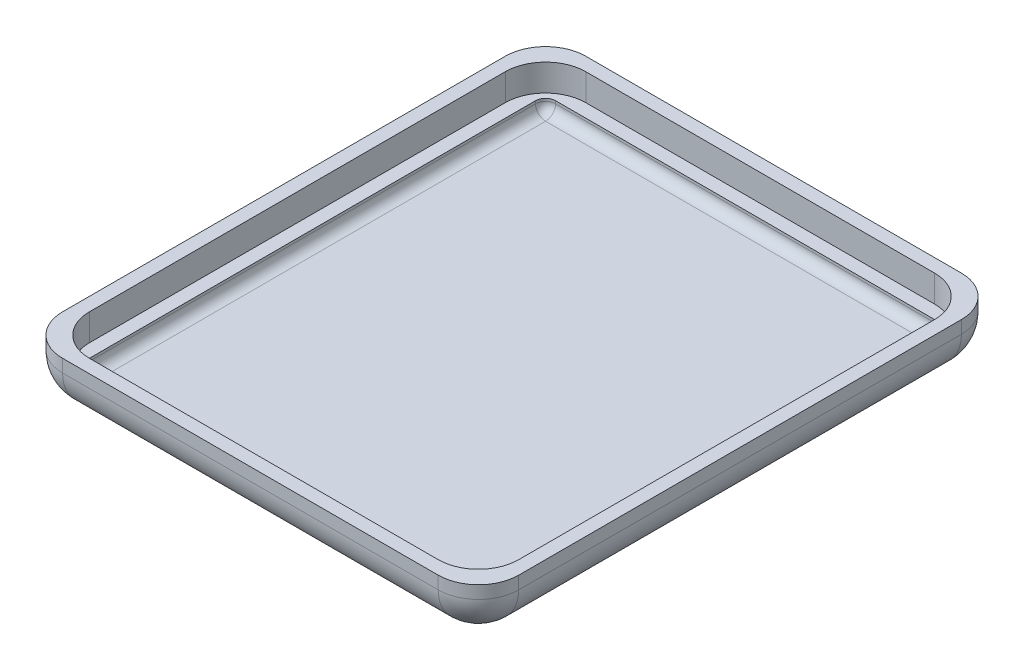
SolidWorks part; units mm, degrees
ref_plane "Piano frontale" through (0, 0, 0) normal (0, 0, 1) x (1, 0, 0)
ref_plane "Piano superiore" through (0, 0, 0) normal (0, 1, 0) x (1, 0, 0)
ref_plane "Piano destro" through (0, 0, 0) normal (1, 0, 0) x (0, 0, -1)
sketch "Schizzo1" plane through (0, 0, 0) normal (0, 1, 0) x (1, 0, 0)
  line L1 (-30.3274, 21.1285) -> (3.6726, 21.1285)
  line L2 (-30.3274, 21.1285) -> (-30.3274, -17.8715)
  line L3 (-30.3274, -17.8715) -> (3.6726, -17.8715)
  line L4 (3.6726, 21.1285) -> (3.6726, -17.8715)
  dimension "D1" = 39
  dimension "D2" = 34
extrude "Estrusione-Estrusione1" add sketch "Schizzo1" along normal blind 3.95
sketch "Schizzo2" plane through (0, 3.95, 0) normal (0, 1, 0) x (1, 0, 0)
  line L0 (3.6726, 21.1285) -> (-30.3274, 21.1285) construction
  line L1 (-29.3274, 20.1285) -> (2.6726, 20.1285)
  line L2 (-29.3274, 20.1285) -> (-29.3274, -16.8715)
  line L3 (-29.3274, -16.8715) -> (2.6726, -16.8715)
  line L4 (2.6726, 20.1285) -> (2.6726, -16.8715)
  line L5 (-30.3274, 21.1285) -> (-30.3274, -17.8715) construction
  dimension "D1" = 37
  dimension "D2" = 32
  dimension "D3" = 1
  dimension "D4" = 1
extrude "Taglio-Estrusione1" cut sketch "Schizzo2" against normal blind 2
sketch "Schizzo3" plane through (0, 1.95, 0) normal (0, 1, 0) x (1, 0, 0)
  line L0 (-29.3274, 20.1285) -> (-29.3274, -16.8715) construction
  line L1 (-28.3274, 19.1285) -> (1.6726, 19.1285)
  line L2 (-28.3274, 19.1285) -> (-28.3274, -15.8715)
  line L3 (-28.3274, -15.8715) -> (1.6726, -15.8715)
  line L4 (1.6726, 19.1285) -> (1.6726, -15.8715)
  line L5 (-29.3274, -16.8715) -> (2.6726, -16.8715) construction
  dimension "D1" = 30
  dimension "D2" = 35
  dimension "D3" = 1
  dimension "D4" = 1
extrude "Taglio-Estrusione2" cut sketch "Schizzo3" against normal blind 0.95
fillet "Raccordo1" radius 3 12 edges at (-13.3274, 0, 17.8715) (3.6726, 1.975, 17.8715) (3.6726, 0, -1.6285) (3.6726, 1.975, -21.1285) (-13.3274, 0, -21.1285) (-30.3274, 1.975, -21.1285) (-30.3274, 0, -1.6285) (-30.3274, 1.975, 17.8715) (-29.3274, 2.95, 16.8715) (2.6726, 2.95, 16.8715) (2.6726, 2.95, -20.1285) (-29.3274, 2.95, -20.1285)
fillet "Raccordo2" radius 0.75 8 edges at (-28.3274, 1.475, -19.1285) (1.6726, 1.475, 15.8715) (-28.3274, 1, -1.6285) (-13.3274, 1, 15.8715) (-28.3274, 1.475, 15.8715) (-13.3274, 1, -19.1285) (1.6726, 1, -1.6285) (1.6726, 1.475, -19.1285)
